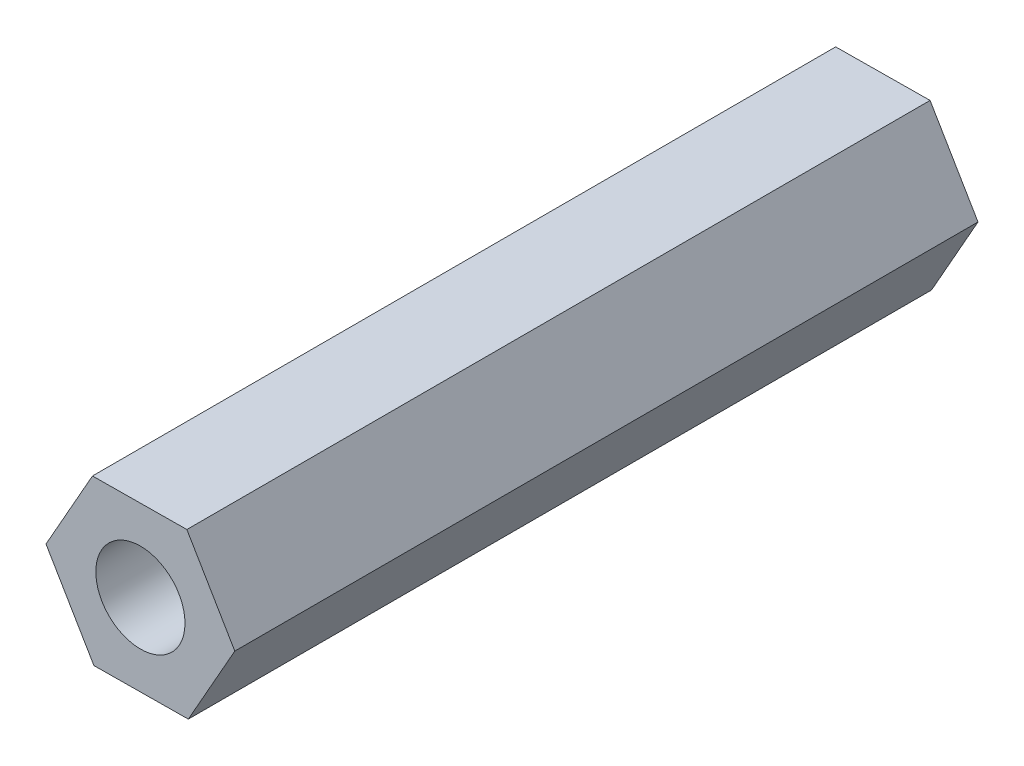
SolidWorks part; units mm, degrees
ref_plane "前视基准面" through (0, 0, 0) normal (0, 0, 1) x (1, 0, 0)
ref_plane "上视基准面" through (0, 0, 0) normal (0, 1, 0) x (1, 0, 0)
ref_plane "右视基准面" through (0, 0, 0) normal (1, 0, 0) x (0, 0, -1)
sketch "草图1" plane through (0, 0, 0) normal (0, 0, 1) x (1, 0, 0)
  line L1 (1.6119, -2.7359) -> (3.1753, 0.028)
  line L2 (3.1753, 0.028) -> (1.5634, 2.7639)
  line L3 (1.5634, 2.7639) -> (-1.6119, 2.7359)
  line L4 (-1.6119, 2.7359) -> (-3.1753, -0.028)
  line L5 (-3.1753, -0.028) -> (-1.5634, -2.7639)
  line L6 (-1.5634, -2.7639) -> (1.6119, -2.7359)
  circle A0 centre (0, 0) radius 2.75 construction
  circle A1 centre (0, 0) radius 1.5
extrude "凸台-拉伸1" add sketch "草图1" along normal blind 25
